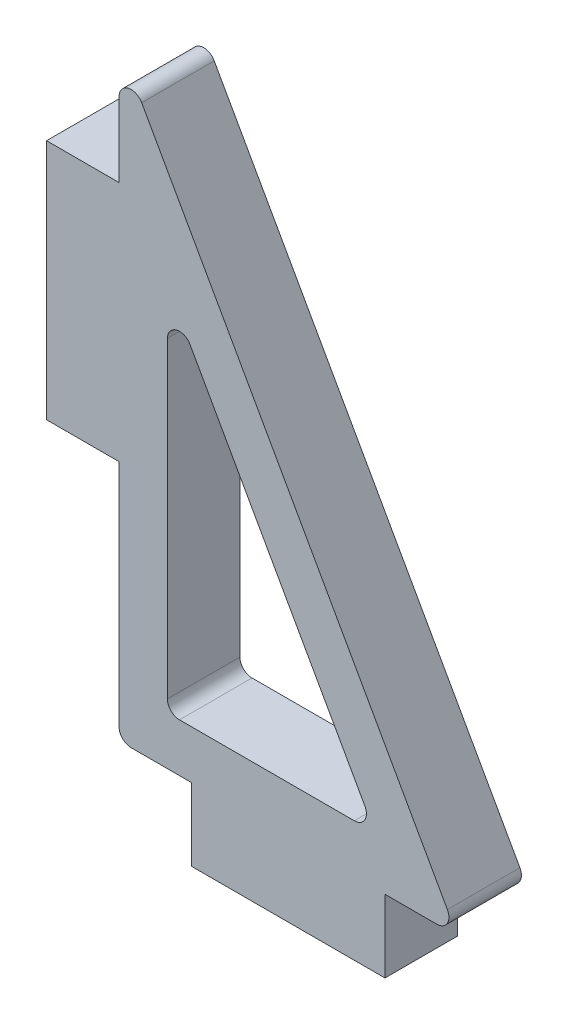
SolidWorks part; units mm, degrees
material "ABS PC"
ref_plane "前视基准面" through (0, 0, 0) normal (0, 0, 1) x (1, 0, 0)
ref_plane "上视基准面" through (0, 0, 0) normal (0, 1, 0) x (1, 0, 0)
ref_plane "右视基准面" through (0, 0, 0) normal (1, 0, 0) x (0, 0, -1)
sketch "草图1" plane through (0, 0, 0) normal (0, 0, 1) x (1, 0, 0)
  line L0 (0.5, 0) -> (3, 0)
  line L1 (3, 0) -> (3, -3)
  line L2 (3, -3) -> (11, -3)
  line L3 (11, -3) -> (11, 0)
  line L4 (11, 0) -> (13.1469, 0)
  line L5 (13.5832, 0.7443) -> (0.9363, 23.3281)
  line L6 (0, 23.0838) -> (0, 20)
  line L7 (0, 20) -> (-3, 20)
  line L8 (-3, 20) -> (-3, 10)
  line L9 (-3, 10) -> (0, 10)
  line L10 (0, 10) -> (0, 0.5)
  arc A0 (0.5, 0) -> (0, 0.5) centre (0.5, 0.5) cw
  arc A1 (13.1469, 0) -> (13.5832, 0.7443) centre (13.1469, 0.5) ccw
  arc A2 (0.9363, 23.3281) -> (0, 23.0838) centre (0.5, 23.0838) ccw
  point P14 (0, 0)
  point P17 (14, 0)
  point P20 (0, 25)
  dimension "D9" = 0.5
  dimension "D1" = 3
  dimension "D2" = 3
  dimension "D3" = 10
  dimension "D4" = 8
  dimension "D5" = 10
  dimension "D6" = 5
  dimension "D7" = 3
  dimension "D8" = 3
extrude "凸台-拉伸2" add sketch "草图1" along normal blind 3
sketch "草图2" plane through (0, 0, 3) normal (0, 0, 1) x (1, 0, 0)
  line L0 (2, 15.4191) -> (2, 2.5)
  line L1 (2.5, 2) -> (9.7347, 2)
  line L2 (10.1709, 2.7443) -> (2.9363, 15.6634)
  line L3 (13.5832, 0.7443) -> (0.9363, 23.3281) construction
  line L4 (0, 10) -> (0, 0.5) construction
  line L5 (11, 0) -> (13.1469, 0) construction
  arc A0 (9.7347, 2) -> (10.1709, 2.7443) centre (9.7347, 2.5) ccw
  arc A1 (2.5, 2) -> (2, 2.5) centre (2.5, 2.5) cw
  arc A2 (2, 15.4191) -> (2.9363, 15.6634) centre (2.5, 15.4191) cw
  dimension "D4" = 0.5
  dimension "D1" = 2
  dimension "D2" = 2
  dimension "D3" = 2
extrude "切除-拉伸1" cut sketch "草图2" against normal through all
